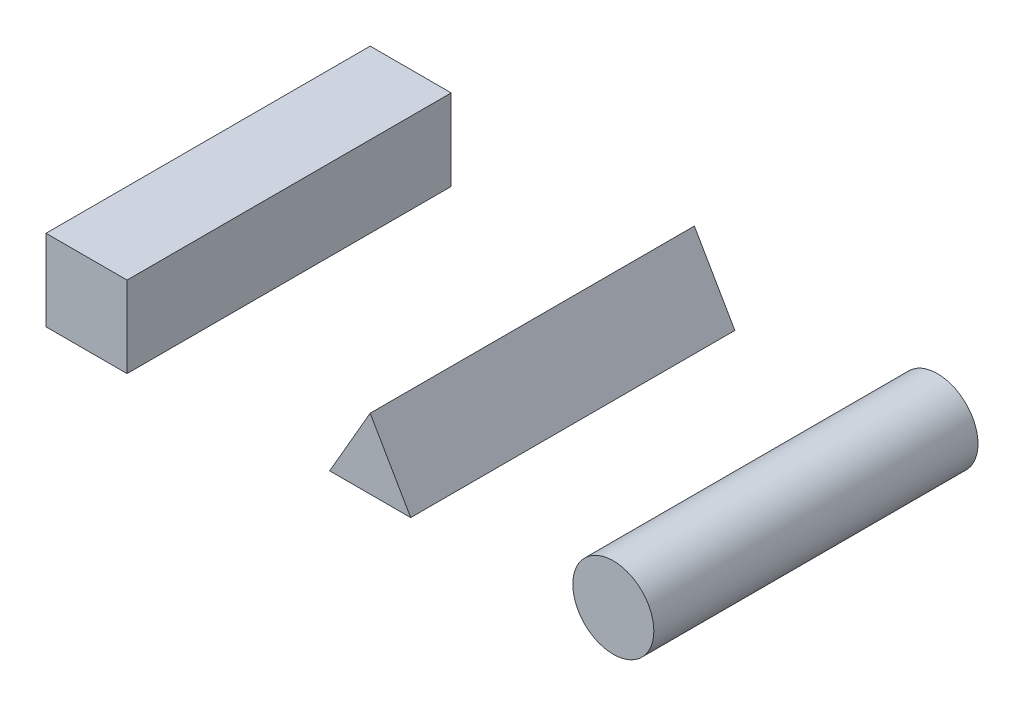
SolidWorks part; units mm, degrees
ref_plane "Front Plane" through (0, 0, 0) normal (0, 0, 1) x (1, 0, 0)
ref_plane "Top Plane" through (0, 0, 0) normal (0, 1, 0) x (1, 0, 0)
ref_plane "Right Plane" through (0, 0, 0) normal (1, 0, 0) x (0, 0, -1)
sketch "Sketch1" plane through (0, 0, 0) normal (0, 0, 1) x (1, 0, 0)
  line L0 (-110, 0) -> (110, 0) construction
  line L1 (-110, 47.5) -> (110, 47.5)
  line L2 (-110, 47.5) -> (-110, -47.5)
  line L3 (-110, -47.5) -> (110, -47.5)
  line L4 (110, 47.5) -> (110, -47.5)
  line L5 (0, 47.5) -> (0, -47.5) construction
  line L6 (-10, -5.7735) -> (0, 11.547)
  line L7 (-80, 10) -> (-60, 10)
  line L8 (-80, 10) -> (-80, -10)
  line L9 (-80, -10) -> (-60, -10)
  line L10 (-60, 10) -> (-60, -10)
  line L11 (-80, 10) -> (-60, -10) construction
  line L12 (-80, -10) -> (-60, 10) construction
  line L14 (-1.3522, 0) -> (0, -1.3522)
  line L18 (0, 11.547) -> (10, -5.7735)
  line L19 (10, -5.7735) -> (-10, -5.7735)
  line L20 (-10, -5.7735) -> (5, 2.8868) construction
  line L21 (10, -5.7735) -> (-5, 2.8868) construction
  line L22 (0, 11.547) -> (0, 0) construction
  circle A0 centre (60, 0) radius 10
  point P10 (-70, 0)
  point P20 (0, 0)
  point P27 (7.7505, -5.3087)
  point P28 (0, 0)
  dimension "D2" = 50
  dimension "cylinder" = 20
  dimension "D1" = 30
  dimension "square2" = 20
  dimension "square" = 20
  dimension "triangle3" = 20
  dimension "triangle2" = 20
  dimension "triangle" = 20
extrude "Boss-Extrude1" add sketch "Sketch1" along normal blind 80
